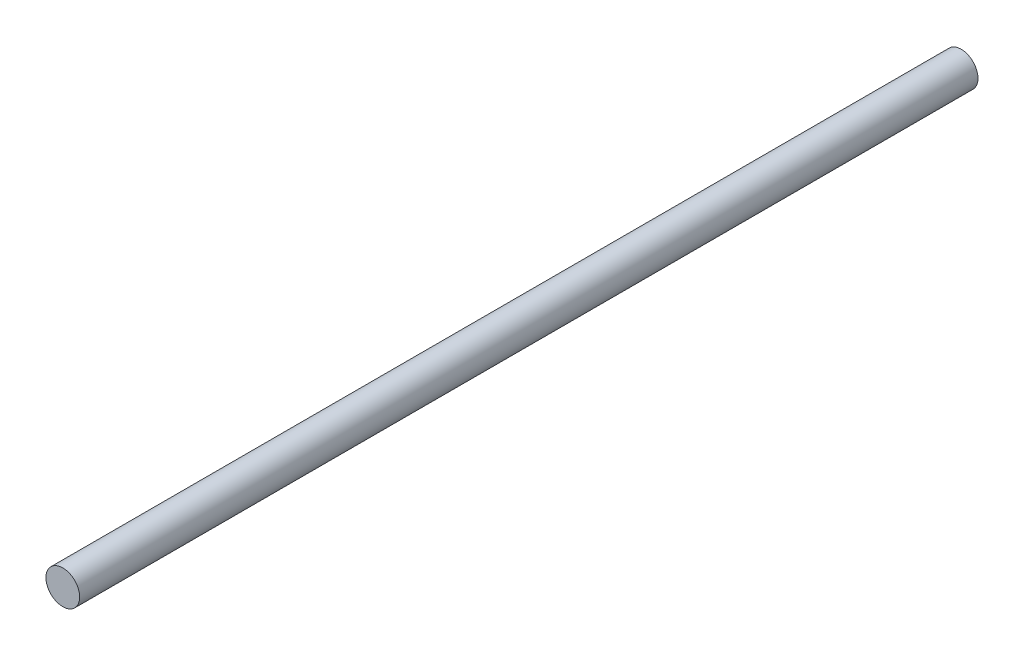
SolidWorks part; units mm, degrees
ref_plane "Piano frontale" through (0, 0, 0) normal (0, 0, 1) x (1, 0, 0)
ref_plane "Piano superiore" through (0, 0, 0) normal (0, 1, 0) x (1, 0, 0)
ref_plane "Piano destro" through (0, 0, 0) normal (1, 0, 0) x (0, 0, -1)
sketch "Schizzo1" plane through (0, 0, 0) normal (0, 0, 1) x (1, 0, 0)
  circle A0 centre (0, 0) radius 7.5
  dimension "D1" = 15
extrude "Estrusione-Estrusione1" add sketch "Schizzo1" along normal mid plane 400
